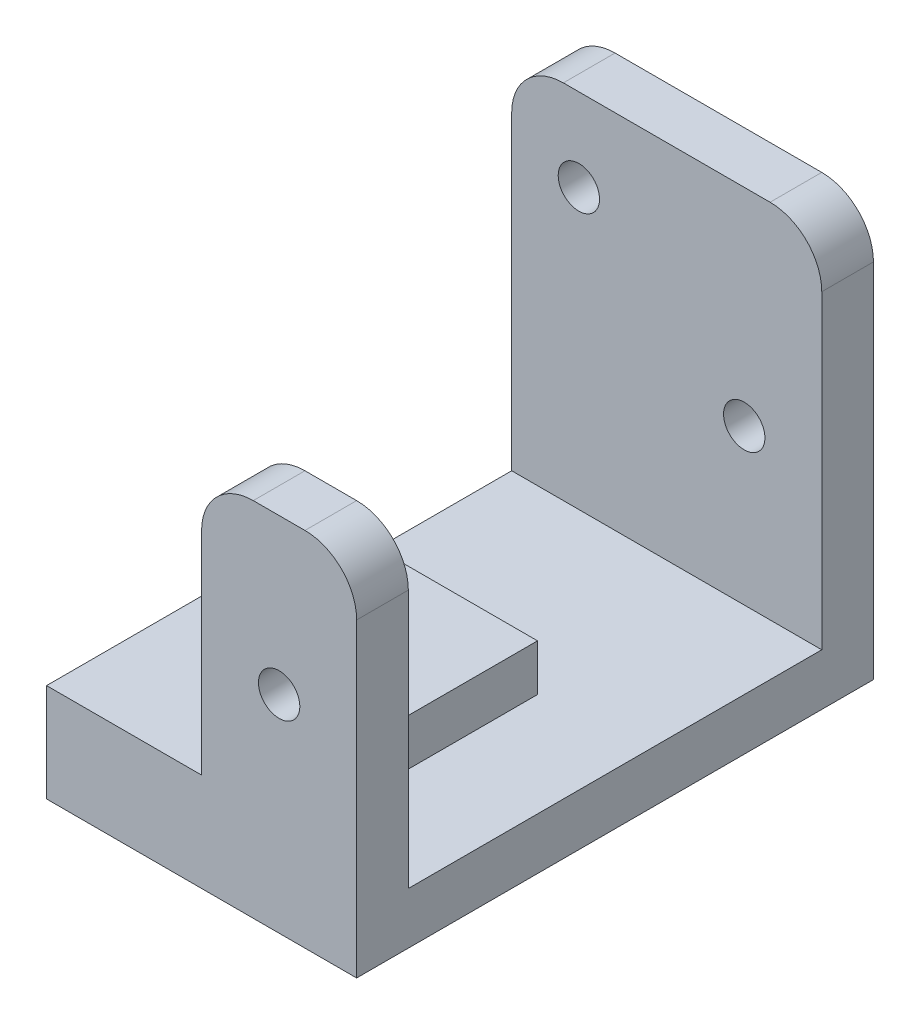
SolidWorks part; units mm, degrees
ref_plane "Front" through (0, 0, 0) normal (0, 0, 1) x (1, 0, 0)
ref_plane "Top" through (0, 0, 0) normal (0, 1, 0) x (1, 0, 0)
ref_plane "Right" through (0, 0, 0) normal (1, 0, 0) x (0, 0, -1)
sketch "Esquisse1" plane through (0, 0, 0) normal (0, 1, 0) x (1, 0, 0)
  line L1 (0, 0) -> (60, 0)
  line L2 (0, 0) -> (0, 100)
  line L3 (0, 100) -> (60, 100)
  line L4 (60, 0) -> (60, 100)
  dimension "D1" = 60
  dimension "D2" = 100
extrude "Boss.-Extru.1" add sketch "Esquisse1" along normal blind 10
sketch "Esquisse2" plane through (0, 10, 0) normal (0, 1, 0) x (1, 0, 0)
  line L1 (30, 0) -> (60, 0)
  line L2 (30, 0) -> (30, 10)
  line L3 (30, 10) -> (60, 10)
  line L4 (0, 100) -> (0, 0)
  line L5 (0, 0) -> (60, 0)
  line L6 (60, 0) -> (60, 100)
  line L7 (60, 100) -> (0, 100)
  line L8 (0, 100) -> (0, 0) construction
  line L9 (0, 0) -> (60, 0) construction
  line L10 (60, 0) -> (60, 100) construction
  line L11 (60, 100) -> (0, 100) construction
  line L12 (60, 0) -> (60, 10)
  dimension "D2" = 10
  dimension "D3" = 30
  dimension "D1" = 0
extrude "Boss.-Extru.2" add sketch "Esquisse2" along normal blind 60
sketch "Esquisse3" plane through (0, 10, 0) normal (0, 1, 0) x (1, 0, 0)
  line L1 (60, 100) -> (0, 100)
  line L2 (60, 100) -> (60, 90)
  line L3 (60, 90) -> (0, 90)
  line L4 (0, 100) -> (0, 90)
  line L8 (60, 10) -> (60, 100)
  line L9 (60, 100) -> (0, 100)
  line L10 (0, 100) -> (0, 0)
  line L11 (0, 0) -> (30, 0)
  line L14 (60, 10) -> (60, 100) construction
  line L15 (60, 100) -> (0, 100) construction
  line L16 (0, 100) -> (0, 0) construction
  line L17 (0, 0) -> (30, 0) construction
  line L20 (30, 0) -> (30, 10)
  line L21 (30, 10) -> (60, 10)
  dimension "D2" = 10
  dimension "D1" = 0
extrude "Boss.-Extru.3" add sketch "Esquisse3" along normal blind 70
sketch "Esquisse8" plane through (0, 10, 0) normal (0, 1, 0) x (1, 0, 0)
  line L0 (0, 0) -> (0, 55)
  line L1 (0, 90) -> (0, 0) construction
  line L4 (40, 55) -> (40, 10)
  line L7 (30, 0) -> (0, 0)
  line L8 (0, 55) -> (40, 55)
  line L13 (30, 10) -> (30, 0)
  line L14 (60, 10) -> (30, 10) construction
  line L15 (40, 10) -> (30, 10)
  dimension "D1" = 55
  dimension "D2" = 40
extrude "Boss.-Extru.4" add sketch "Esquisse8" along normal blind 9
sketch "Esquisse6" plane through (0, 0, -100) normal (0, 0, -1) x (-1, 0, 0)
  line L0 (-60, 0) -> (0, 0) construction
  line L1 (-60, 80) -> (-60, 0) construction
  line L2 (0, 10) -> (-60, 10) construction
  line L3 (0, 10) -> (-60, 10) construction
  line L5 (-40, 19) -> (0, 19) construction
  line L6 (-40, 19) -> (0, 19) construction
  circle A0 centre (-45, 40) radius 4
  circle A1 centre (-13, 64) radius 4
  dimension "D1" = 8
  dimension "D4" = 8
  dimension "D2" = 40
  dimension "D3" = 15
  dimension "D5" = 40
  dimension "D6" = 45
extrude "Enlèv. mat.-Extru.2" cut sketch "Esquisse6" against normal through all
fillet "Congé1" radius 10 4 edges at (0, 80, -95) (60, 80, -95) (30, 70, -5) (60, 70, -5)
